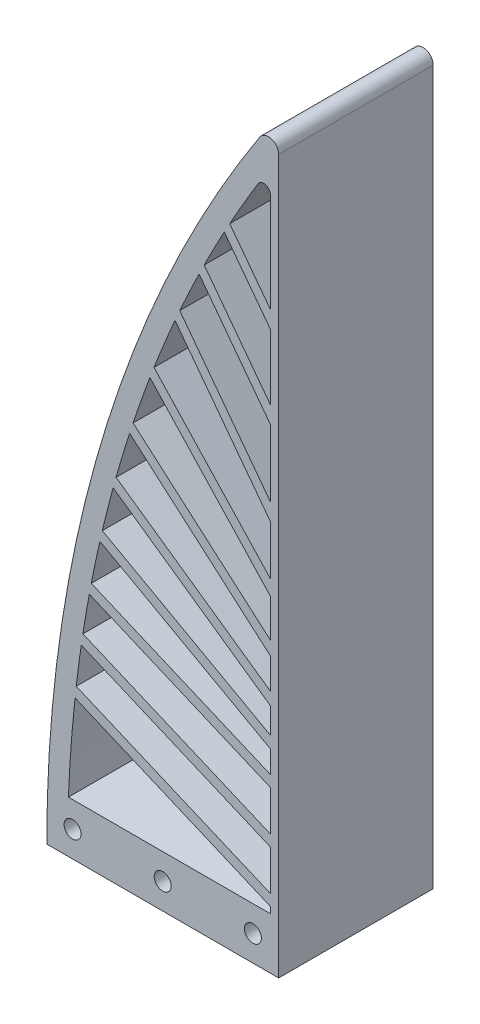
SolidWorks part; units mm, degrees
material "Silicon"
ref_plane "Front Plane" through (0, 0, 0) normal (0, 0, 1) x (1, 0, 0)
ref_plane "Top Plane" through (0, 0, 0) normal (0, 1, 0) x (1, 0, 0)
ref_plane "Right Plane" through (0, 0, 0) normal (1, 0, 0) x (0, 0, -1)
sketch "Sketch1" plane through (0, 0, 0) normal (0, 1, 0) x (1, 0, 0)
  line L1 (-9.5, 8) -> (9.5, 8) construction
  line L2 (-9.5, 8) -> (-9.5, -8) construction
  line L3 (-9.5, -8) -> (9.5, -8) construction
  line L4 (9.5, 8) -> (9.5, -8) construction
  line L5 (-9.5, 8) -> (9.5, -8) construction
  line L6 (-9.5, -8) -> (9.5, 8) construction
  line L7 (12, 10.5) -> (-12, 10.5)
  line L8 (12, 10.5) -> (12, -10.5)
  line L9 (12, -10.5) -> (-12, -10.5)
  line L10 (-12, 10.5) -> (-12, -10.5)
  line L11 (12, 10.5) -> (-12, -10.5) construction
  line L12 (12, -10.5) -> (-12, 10.5) construction
  circle A0 centre (-9.5, 8) radius 1.625
  circle A1 centre (9.5, 8) radius 1.625
  circle A2 centre (9.5, -8) radius 1.625
  circle A3 centre (-9.5, -8) radius 1.625
  point P0 (0, 0)
  point P10 (0, 0)
  dimension "D3" = 3.25
  dimension "D1" = 24
  dimension "D2" = 21
  dimension "D4" = 19
  dimension "D5" = 16
extrude "Boss-Extrude1" [suppressed] add sketch "Sketch1" along normal blind 7.5
sketch "Sketch5" plane through (0, 0, 0) normal (0, 0, 1) x (1, 0, 0)
  line L0 (0, 0) -> (0, 138.4056)
  line L1 (-45, 0) -> (0, 0)
  line L2 (-1.6, 10) -> (-40.8016, 10)
  line L98 (-1.6, 10) -> (-1.6, 130.8055)
  line L99 (-45, 0) -> (-45, 5) construction
  line L102 (-40.9683, 4) -> (-4, 4) construction
  line L103 (-4, 4) -> (-4, 131.4809) construction
  line L104 (0, 0) -> (0, 145) construction
  arc A1 (-3.6773, 139.4949) -> (-45, 0) centre (211.1111, 0) ccw
  arc A24 (-4, 131.4809) -> (-40.8016, 10) centre (211.1111, 0) ccw
  arc A25 (-4, 131.4809) -> (-40.9683, 4) centre (211.1111, 0) ccw construction
  arc A26 (-1.6, 130.8055) -> (-4, 131.4809) centre (-2.895, 130.8055) ccw
  arc A27 (0, 145) -> (-45, 0) centre (211.1111, 0) ccw construction
  arc A28 (0, 138.4056) -> (-3.6773, 139.4949) centre (-2, 138.4056) ccw
  point P16 (0, 145)
  dimension "D7" = 2
  dimension "D2" = 145
  dimension "D5" = 10
  dimension "D6" = 1.6
  dimension "D1" = 5
  dimension "D3" = 45
  dimension "D4" = 4
extrude "Boss-Extrude4" add sketch "Sketch5" along normal blind 30
sketch "Sketch10" plane through (0, 0, 30) normal (0, 0, 1) x (1, 0, 0)
  line L0 (-40.5534, 15) -> (-1.6, 15)
  line L1 (-1.6, 10) -> (-1.6, 130.8055) construction
  line L2 (-1.6, 16.6) -> (-40.4529, 16.6)
  line L3 (-40.8016, 10) -> (-1.6, 10) construction
  line L4 (0, 10) -> (75, 10) construction
  line L5 (0, 0) -> (0, 138.4056) construction
  line L6 (-39.3977, 27.0512) -> (-0.6577, 22.9795)
  line L7 (-0.4905, 24.5707) -> (-39.1306, 28.632)
  line L8 (-36.9887, 38.9156) -> (1.1135, 30.8168)
  line L9 (1.4461, 32.3818) -> (-36.5578, 40.4598)
  line L10 (-33.3527, 50.4632) -> (3.6942, 38.426)
  line L11 (4.1886, 39.9477) -> (-32.7627, 51.9539)
  line L12 (-28.5296, 61.5675) -> (7.0561, 45.7238)
  line L13 (7.7069, 47.1854) -> (-27.787, 62.9883)
  line L14 (-22.5722, 72.1068) -> (11.1625, 52.6301)
  line L15 (11.9625, 54.0158) -> (-21.6851, 73.4422)
  line L20 (0, 68.0707) -> (75, 10) construction
  line L21 (-1.6, 69.3095) -> (-25.2762, 87.6415)
  line L22 (-1.6, 70.9537) -> (-24.7996, 88.9166)
  line L23 (3.8607, 75.76) -> (-18.1278, 96.0857)
  line L24 (4.0039, 77.3979) -> (-17.5418, 97.3144)
  line L25 (9.8627, 81.7099) -> (-10.2705, 103.8747)
  line L26 (10.1482, 83.3291) -> (-9.5797, 105.0477)
  line L27 (16.3605, 87.1142) -> (-1.7643, 110.9493)
  line L28 (16.7861, 88.7023) -> (-0.9739, 112.0576)
  line L29 (23.3046, 91.9315) -> (7.3261, 117.2556)
  line L30 (23.8669, 93.4765) -> (8.2101, 118.2908)
  arc A0 (-4, 131.4809) -> (-40.8016, 10) centre (211.1111, 0) ccw construction
  arc A1 (-4, 131.4809) -> (-40.8016, 10) centre (211.1111, 0) ccw
  point P54 (75, 10)
  point P67 (75, 10)
  dimension "D1" = 1.6
  dimension "D2" = 5
  dimension "D5" = 6
  dimension "D6" = 1.3
  dimension "D9" = 5
  dimension "D7" = 7.75
  dimension "D3" = 121.4809
  dimension "D4" = 6
  dimension "D8" = 5
sketch "Sketch11" plane through (0, 0, 30) normal (0, 0, 1) x (1, 0, 0)
  line L0 (-40.5534, 15) -> (-1.6, 15)
  line L1 (-1.6, 10) -> (-1.6, 130.8055) construction
  line L2 (-1.6, 15) -> (-1.6, 16.6)
  line L3 (-40.4529, 16.6) -> (-1.6, 16.6)
  line L4 (-39.5429, 27.0665) -> (-1.6, 23.0785)
  line L5 (-39.3977, 27.0512) -> (-0.6577, 22.9795) construction
  line L6 (-39.366, 28.6567) -> (-1.6, 24.6873)
  line L7 (-0.4905, 24.5707) -> (-39.1306, 28.632) construction
  line L8 (-37.9465, 39.1192) -> (-1.6, 31.3935)
  line L9 (-37.6929, 40.7011) -> (-1.6, 33.0293)
  line L10 (1.4461, 32.3818) -> (-36.5578, 40.4598) construction
  line L11 (-36.9887, 38.9156) -> (1.1135, 30.8168) construction
  line L12 (-35.7383, 51.2384) -> (-1.6, 40.1462)
  line L13 (-33.3527, 50.4632) -> (3.6942, 38.426) construction
  line L14 (-35.4063, 52.8128) -> (-1.6, 41.8285)
  line L15 (4.1886, 39.9477) -> (-32.7627, 51.9539) construction
  line L16 (-32.8718, 63.5008) -> (-1.6, 49.5777)
  line L17 (-28.5296, 61.5675) -> (7.0561, 45.7238) construction
  line L18 (-32.4585, 65.0682) -> (-1.6, 51.3291)
  line L19 (7.7069, 47.1854) -> (-27.787, 62.9883) construction
  line L29 (-25.2762, 87.6415) -> (-1.6, 69.3095)
  line L31 (-24.7996, 88.9166) -> (-1.6, 70.9537)
  line L33 (-1.6, 61.8461) -> (-28.7801, 77.5385)
  line L35 (-29.2786, 75.9788) -> (-1.6, 59.9985)
  line L36 (-20.899, 98.6474) -> (-1.6, 80.8077)
  line L37 (3.8607, 75.76) -> (-18.1278, 96.0857) construction
  line L38 (-20.3557, 99.9155) -> (-1.6, 82.578)
  line L39 (4.0039, 77.3979) -> (-17.5418, 97.3144) construction
  line L40 (-15.7708, 109.93) -> (-1.6, 94.3293)
  line L41 (9.8627, 81.7099) -> (-10.2705, 103.8747) construction
  line L42 (-15.1571, 111.1878) -> (-1.6, 96.2628)
  line L43 (10.1482, 83.3291) -> (-9.5797, 105.0477) construction
  line L44 (-9.7895, 121.5028) -> (-1.6, 110.7332)
  line L45 (16.3605, 87.1142) -> (-1.7643, 110.9493) construction
  line L46 (-9.1013, 122.7456) -> (-1.6, 112.8809)
  line L47 (16.7861, 88.7023) -> (-0.9739, 112.0576) construction
  line L48 (-1.6, 23.0785) -> (-1.6, 24.6873)
  line L49 (-1.6, 31.3935) -> (-1.6, 33.0293)
  line L50 (-1.6, 40.1462) -> (-1.6, 41.8285)
  line L51 (-1.6, 49.5777) -> (-1.6, 51.3291)
  line L53 (-1.6, 110.7332) -> (-1.6, 112.8809)
  line L54 (-1.6, 94.3293) -> (-1.6, 96.2628)
  line L55 (-1.6, 80.8077) -> (-1.6, 82.578)
  line L59 (-22.5722, 72.1068) -> (11.1625, 52.6301) construction
  line L60 (11.9625, 54.0158) -> (-21.6851, 73.4422) construction
  line L61 (-1.6, 59.9985) -> (-1.6, 61.8461)
  line L62 (-2.8376, 133.364) -> (-1.6, 131.4025)
  line L63 (-2.0713, 134.5856) -> (-1.6, 133.8387)
  line L64 (23.8669, 93.4765) -> (8.2101, 118.2908) construction
  line L65 (23.3046, 91.9315) -> (7.3261, 117.2556) construction
  line L66 (-1.6, 133.8387) -> (-1.6, 131.4025)
  arc A0 (-4, 131.4809) -> (-40.8016, 10) centre (211.1111, 0) ccw construction
  arc A2 (-40.4529, 16.6) -> (-40.5534, 15) centre (211.1111, 0) ccw
  arc A8 (-20.3557, 99.9155) -> (-20.899, 98.6474) centre (211.1111, 0) ccw
  arc A13 (-2.0713, 134.5856) -> (-2.8376, 133.364) centre (211.1111, 0) ccw
  arc A14 (-40.4529, 16.6) -> (-40.5534, 15) centre (211.1111, 0) ccw
  arc A15 (-39.366, 28.6567) -> (-39.5429, 27.0665) centre (211.1111, 0) ccw
  arc A16 (-37.6929, 40.7011) -> (-37.9465, 39.1192) centre (211.1111, 0) ccw
  arc A17 (-35.4063, 52.8128) -> (-35.7383, 51.2384) centre (211.1111, 0) ccw
  arc A18 (-32.4585, 65.0682) -> (-32.8718, 63.5008) centre (211.1111, 0) ccw
  arc A19 (-28.7801, 77.5385) -> (-29.2786, 75.9788) centre (211.1111, 0) ccw
  arc A20 (-24.7996, 88.9166) -> (-25.2762, 87.6415) centre (211.1111, 0) ccw
  arc A21 (-20.3557, 99.9155) -> (-20.899, 98.6474) centre (211.1111, 0) ccw
  arc A22 (-15.1571, 111.1878) -> (-15.7708, 109.93) centre (211.1111, 0) ccw
  arc A23 (-9.1013, 122.7456) -> (-9.7895, 121.5028) centre (211.1111, 0) ccw
sketch "Sketch12" plane through (0, 0, 30) normal (0, 0, 1) x (1, 0, 0)
  line L0 (-40, 5) -> (-22.5, 5) construction
  line L1 (-40.8016, 10) -> (-1.6, 10) construction
  line L2 (-22.5, 0) -> (-22.5, 10) construction
  line L3 (-45, 0) -> (0, 0) construction
  line L4 (-22.5, 5) -> (-5, 5) construction
  line L6 (-5, 5) -> (0, 5) construction
  line L7 (0, 0) -> (0, 138.4056) construction
  circle A1 centre (-40, 5) radius 1.65
  circle A2 centre (-22.5, 5) radius 1.65
  circle A3 centre (-5, 5) radius 1.65
  dimension "D1" = 3.3
  dimension "D2" = 17.5
extrude "Cut-Extrude1" cut sketch "Sketch12" against normal through all
sketch "Sketch14" plane through (0, 0, 30) normal (0, 0, 1) x (1, 0, 0)
  line L1 (48.4, 10) -> (-108.8813, 76.762)
  line L6 (48.4, 10) -> (49.1815, 11.841)
  line L7 (-108.8813, 76.762) -> (-108.0998, 78.603)
  line L8 (49.1815, 11.841) -> (-108.0998, 78.603)
  line L9 (-40.8016, 10) -> (-1.6, 10) construction
  dimension "D1" = 0
  dimension "D2" = 2
  dimension "D3" = 50
  dimension "D4" = 23
sketch "Sketch17" plane through (0, 0, 30) normal (0, 0, 1) x (1, 0, 0)
  line L0 (-45, 0) -> (0, 0)
  line L1 (0, 0) -> (0, 138.4056)
  line L3 (-109.1292, -31.174) -> (890.8708, -18.3863)
  line L4 (890.8708, -18.3863) -> (884.1337, 508.4542)
  line L5 (884.1337, 508.4542) -> (-120.6382, 868.826)
  line L6 (-120.6382, 868.826) -> (-717.4627, 272.0014)
  line L7 (-717.4627, 272.0014) -> (-109.1292, -31.174)
  arc A1 (0, 138.4056) -> (-2.7696, 140.2516) centre (-2, 138.4056) ccw
  arc A3 (-2.7696, 140.2516) -> (-45, 0) centre (33.6937, 52.7886) ccw
  dimension "D1" = 900
  dimension "D2" = 1000
extrude "Cut-Extrude2" cut sketch "Sketch17" against normal blind 20
sketch "Sketch18" plane through (0, 0, 30) normal (0, 0, 1) x (1, 0, 0)
  line L0 (-45, 0) -> (0, 0)
  line L1 (0, 0) -> (0, 138.4056)
  line L2 (10.5677, -7.1526) -> (26.572, 318.7821)
  line L3 (26.572, 318.7821) -> (-234.7297, 306.4711)
  line L4 (-234.7297, 306.4711) -> (-205.7988, -46.8557)
  line L5 (-205.7988, -46.8557) -> (10.5677, -7.1526)
  arc A0 (0, 138.4056) -> (-3.6773, 139.4949) centre (-2, 138.4056) ccw
  arc A1 (-3.6773, 139.4949) -> (-45, 0) centre (211.1111, 0) ccw
extrude "Cut-Extrude3" cut sketch "Sketch18" against normal blind 30
extrude "Boss-Extrude5" add sketch "Sketch14" against normal blind 30
pattern_circular "CirPattern1" count 6 every 6 about axis through (49.1815, 11.841, 0) along (0, 0, 1) of "Boss-Extrude5"
pattern_linear "LPattern2" count 3 spacing 10 along (0, -1, 0) of "Boss-Extrude5"
sketch "Sketch20" plane through (0, 0, 30) normal (0, 0, 1) x (1, 0, 0)
  line L0 (-45, 0) -> (0, 0)
  line L1 (0, 0) -> (0, 138.4056)
  line L2 (77.4758, -29.0172) -> (-265.5513, 6.5235)
  line L3 (-265.5513, 6.5235) -> (-137.3654, 367.5206)
  line L4 (-137.3654, 367.5206) -> (154.1478, 113.1454)
  line L5 (154.1478, 113.1454) -> (77.4758, -29.0172)
  arc A0 (0, 138.4056) -> (-3.6773, 139.4949) centre (-2, 138.4056) ccw
  arc A1 (-3.6773, 139.4949) -> (-45, 0) centre (211.1111, 0) ccw
extrude "Cut-Extrude4" cut sketch "Sketch20" against normal blind 30
sketch "Sketch21" plane through (0, 0, 30) normal (0, 0, 1) x (1, 0, 0)
  line L0 (-1.6, 92.2303) -> (-0.0027, 93.4339)
  line L1 (-1.6, 92.2303) -> (-25.6726, 124.1757)
  line L2 (-0.0027, 93.4339) -> (-24.0753, 125.3793)
  line L3 (-25.6726, 124.1757) -> (-24.0753, 125.3793)
  line L4 (-1.6, 79.2303) -> (-1.6, 130.8055) construction
  line L5 (-1.6, 79.2303) -> (-19.1903, 102.5733) construction
  dimension "D1" = 2
  dimension "D2" = 0
  dimension "D3" = 40
  dimension "D4" = 13
extrude "Boss-Extrude7" add sketch "Sketch21" against normal blind 30
pattern_linear "LPattern3" count 2 spacing 16 along (0, 1, 0) of "Boss-Extrude7"
sketch "Sketch22" plane through (0, 0, 30) normal (0, 0, 1) x (1, 0, 0)
  line L0 (0, 138.4056) -> (0, 0)
  line L1 (0, 0) -> (-45, 0)
  line L2 (-56.499, -6.7157) -> (29.9264, -13.4211)
  line L3 (29.9264, -13.4211) -> (17.2606, 198.6687)
  line L4 (17.2606, 198.6687) -> (-109.3973, 188.7347)
  line L5 (-109.3973, 188.7347) -> (-56.499, -6.7157)
  arc A0 (0, 138.4056) -> (-3.6773, 139.4949) centre (-2, 138.4056) ccw
  arc A1 (-3.6773, 139.4949) -> (-45, 0) centre (211.1111, 0) ccw
extrude "Cut-Extrude5" cut sketch "Sketch22" against normal blind 30
equation "\"Middle Finger Width\"= 30mm"
equation "\"Finger Length\"= 45"
equation "\"Finger Height\"= \"Finger Length\" * 3.5"
equation "\"D3@Sketch5\"=\"Finger Length\""
equation "\"Base Height\"= 10mm"
equation "\"D1@Sketch5\"= \"Base Height\" / 2"
equation "\"D5@Sketch5\"= \"Base Height\""
equation "\"Thick Walls\"= 1.6mm"
equation "\"Thin Walls\"= 1.3mm"
equation "\"D6@Sketch5\"=\"Thick Walls\""
equation "\"D2@Sketch10\"=\"Base Height\"/2"
equation "\"D1@Sketch10\"=\"Thick Walls\" "
equation "\"D6@Sketch10\"=\"Thin Walls\""
equation "\"D1@Boss-Extrude4\"=2 * \"Middle Finger Width\" /30mm"
equation "\"Outer Finger Width\"= 2 * \"Middle Finger Width\" / 3"
